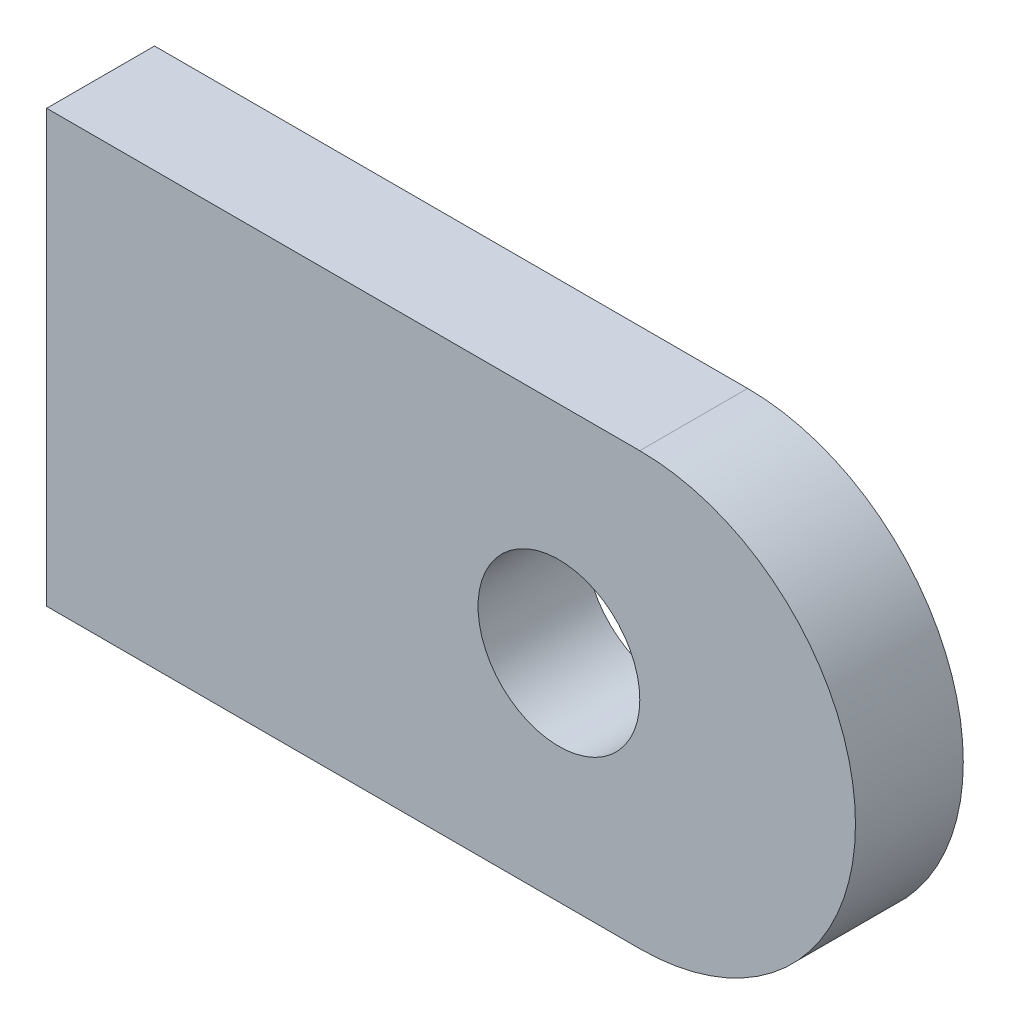
SolidWorks part; units mm, degrees
ref_plane "Front Plane" through (0, 0, 0) normal (0, 0, 1) x (1, 0, 0)
ref_plane "Top Plane" through (0, 0, 0) normal (0, 1, 0) x (1, 0, 0)
ref_plane "Right Plane" through (0, 0, 0) normal (1, 0, 0) x (0, 0, -1)
sketch "Sketch1" plane through (0, 0, 0) normal (0, 0, 1) x (1, 0, 0)
  line L1 (275, -200) -> (-275, -200)
  line L2 (275, -200) -> (275, 200)
  line L3 (275, 200) -> (-275, 200)
  line L4 (-275, -200) -> (-275, 200)
  line L5 (275, -200) -> (-275, 200) construction
  line L6 (275, 200) -> (-275, -200) construction
  arc A0 (275, 200) -> (275, -200) centre (275, 0) cw
  circle A1 centre (200, 0) radius 75
  point P0 (0, 0)
  point P9 (475, 0)
  dimension "D3" = 150
  dimension "D1" = 400
  dimension "D2" = 550
  dimension "D4" = 475
  dimension "D5" = 750
extrude "Boss-Extrude1" add sketch "Sketch1" along normal blind 100 contours L2 A1 L3 L4 L1 | A0 L2
